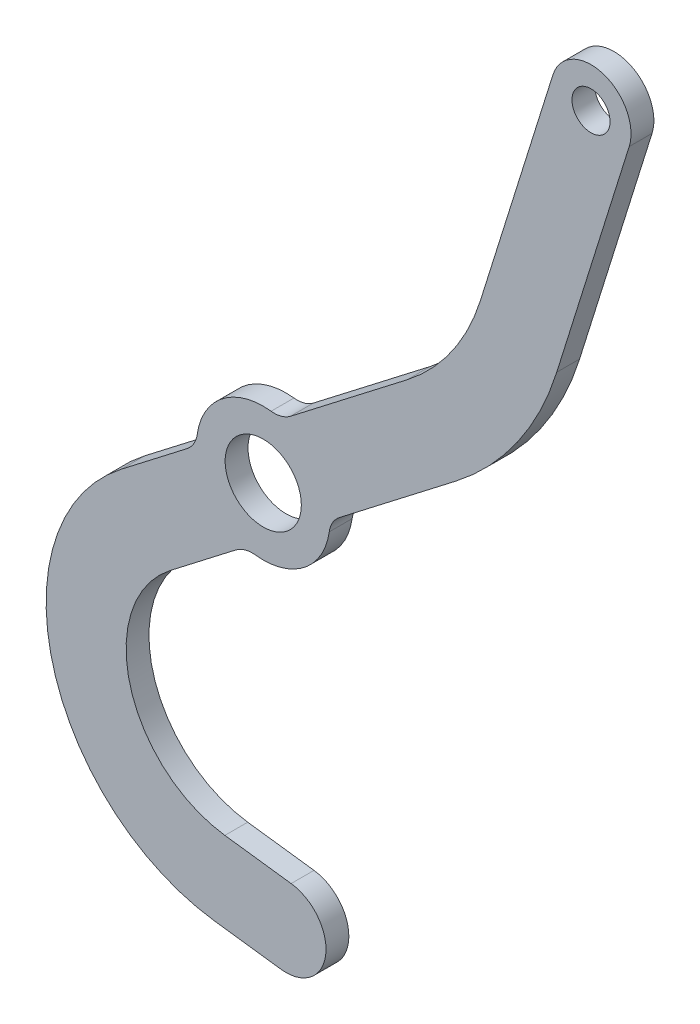
SolidWorks part; units mm, degrees
ref_plane "Front Plane" through (0, 0, 0) normal (0, 0, 1) x (1, 0, 0)
ref_plane "Top Plane" through (0, 0, 0) normal (0, 1, 0) x (1, 0, 0)
ref_plane "Right Plane" through (0, 0, 0) normal (1, 0, 0) x (0, 0, -1)
sketch "Sketch1" plane through (0, 0, 0) normal (0, 0, 1) x (1, 0, 0)
  line L0 (58.1231, 76.5966) -> (85.3027, 163.4913)
  line L1 (113.9348, 154.5355) -> (86.7552, 67.6408)
  line L2 (30.6168, 37.1218) -> (-13.1, 3.4178)
  line L3 (48.934, 13.363) -> (5.2172, -20.341)
  line L4 (-51.8979, -26.4941) -> (-76.5489, -45.4991)
  line L5 (-33.5807, -50.2529) -> (-58.2318, -69.2579)
  line L6 (-37.7335, -145.0652) -> (-12.8722, -148.2805)
  line L7 (-41.5813, -174.8174) -> (-16.72, -178.0327)
  arc A0 (85.3027, 163.4913) -> (113.9348, 154.5355) centre (99.6187, 159.0134) cw
  arc A1 (58.1231, 76.5966) -> (30.6168, 37.1218) centre (-18.229, 100.4786) cw
  arc A2 (86.7552, 67.6408) -> (48.934, 13.363) centre (-18.229, 100.4786) cw
  arc A3 (-13.1, 3.4178) -> (-20.387, 1.4074) centre (-19.2057, 11.3374) cw
  arc A4 (-20.387, 1.4074) -> (-48.0999, -19.9582) centre (-23.3404, -23.4176) ccw
  arc A5 (-48.0999, -19.9582) -> (-51.8979, -26.4941) centre (-58.0037, -18.5745) cw
  arc A6 (5.2172, -20.341) -> (1.4191, -26.8769) centre (11.3229, -28.2606) ccw
  arc A7 (1.4191, -26.8769) -> (-26.2937, -48.2425) centre (-23.3404, -23.4176) cw
  arc A8 (-26.2937, -48.2425) -> (-33.5807, -50.2529) centre (-27.475, -58.1725) ccw
  arc A9 (-58.2318, -69.2579) -> (-37.7335, -145.0652) centre (-32.2824, -102.9162) ccw
  arc A10 (-76.5489, -45.4991) -> (-41.5813, -174.8174) centre (-32.2824, -102.9162) ccw
  arc A11 (-12.8722, -148.2805) -> (-16.72, -178.0327) centre (-14.7961, -163.1566) cw
extrude "Boss-Extrude1" add sketch "Sketch1" along normal blind 8.5714
scale "Scale1" scale about centroid uniform scaling yes scale factor 0.35
sketch "Sketch4" plane through (0, 0, 5.7857) normal (0, 0, 1) x (1, 0, 0)
  circle A0 centre (-9.5523, -20.2036) radius 5
  circle A1 centre (33.4834, 43.6473) radius 2.5
extrude "Cut-Extrude1" cut sketch "Sketch4" against normal up to surface (3 mm away) up to face at (-2.2355, -19.8248, 2.7857)
